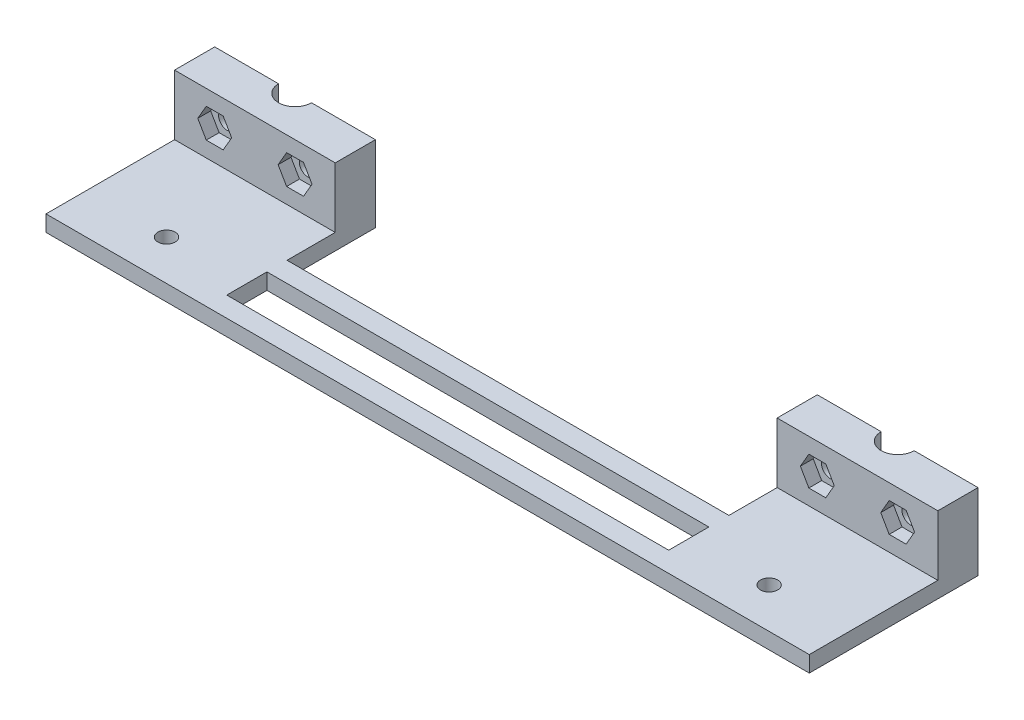
SolidWorks part; units mm, degrees
material "ABS"
ref_plane "Ebene vorne" through (0, 0, 0) normal (0, 0, 1) x (1, 0, 0)
ref_plane "Ebene oben" through (0, 0, 0) normal (0, 1, 0) x (1, 0, 0)
ref_plane "Ebene rechts" through (0, 0, 0) normal (1, 0, 0) x (0, 0, -1)
sketch "Skizze1" plane through (0, 0, 0) normal (0, 1, 0) x (1, 0, 0)
  line L0 (0, 0) -> (75, 0)
  line L1 (0, 0) -> (-75, 0)
  line L2 (55, -10) -> (55, -5)
  line L3 (55, 10) -> (55, 5)
  line L4 (55, -5) -> (55, 5)
  line L5 (-95, 32) -> (-75, 32)
  line L6 (-75, 32) -> (-75, 0)
  line L7 (-75, 32) -> (-55, 32)
  line L8 (-55, 5) -> (-55, 10)
  line L9 (-55, -10) -> (-95, -10)
  line L10 (75, 0) -> (75, 32)
  line L11 (75, 32) -> (55, 32)
  line L12 (-95, -10) -> (-95, 32)
  line L13 (-95, 32) -> (-94.8334, 32.0924)
  line L14 (-55, 32) -> (-55, 10)
  line L15 (95, 32) -> (75, 32)
  line L16 (0, 0) -> (0, 5)
  line L17 (0, 5) -> (-55, 5)
  line L18 (0, 0) -> (0, -5)
  line L19 (0, -5) -> (55, -5)
  line L20 (0, -5) -> (-55, -5)
  line L21 (0, 5) -> (55, 5)
  line L22 (0, 5) -> (0, 10)
  line L23 (0, 10) -> (-55, 10)
  line L24 (0, 10) -> (55, 10)
  line L25 (0, -5) -> (0, -10)
  line L26 (0, -10) -> (55, -10)
  line L27 (0, -10) -> (-55, -10)
  line L28 (-55, 5) -> (-55, -5)
  line L29 (-55, -10) -> (-55, -5)
  line L30 (55, 32) -> (55, 10)
  line L31 (-75, 32) -> (-75, 27.9)
  line L32 (55, -10) -> (95, -10)
  line L33 (95, -10) -> (95, 32)
  line L34 (55, -5) -> (55, 5)
  circle A0 centre (-75, 0) radius 2.15
  circle A1 centre (75, 0) radius 2.15
  arc A2 (-70.9, 32) -> (-79.1, 32) centre (-75, 32) cw
  arc A3 (79.1, 32) -> (70.9, 32) centre (75, 32) cw
  dimension "D5" = 4.3
  dimension "D10" = 4.3
  dimension "D2" = 32
  dimension "D3" = 32
  dimension "D7" = 20
  dimension "D8" = 20
  dimension "D9" = 20
  dimension "D11" = 75
  dimension "D12" = 75
  dimension "D13" = 20
extrude "Aufsatz-Linear austragen1" add sketch "Skizze1" along normal blind 4 contours L6 A2 L5 L12 L9 L29 L28 L1 A0 | L7 A2 L6 A0 L1 L28 L8 L14 | L22 L23 L8 L17 | L24 L22 L21 L3 | L10 A3 L11 L30 L3 L4 L0 A1 | L15 A3 L10 A1 L0 L4 L2 L32 L33 | L25 L26 L2 L19 | L29 L27 L25 L20
sketch "Skizze2" plane through (0, 4, 0) normal (0, 1, 0) x (1, 0, 0)
  line L0 (-95, 32) -> (-95, 22)
  line L1 (-95, -10) -> (-95, 32) construction
  line L2 (-95, 22) -> (-55, 22)
  line L3 (-55, 32) -> (-55, 10) construction
  line L4 (-55, 22) -> (-55, 32)
  line L5 (-55, 32) -> (-70.9, 32)
  line L6 (-79.1, 32) -> (-95, 32)
  line L7 (55, 32) -> (55, 22)
  line L8 (55, 32) -> (55, 10) construction
  line L9 (55, 22) -> (95, 22)
  line L10 (95, -10) -> (95, 32) construction
  line L11 (95, 22) -> (95, 32)
  line L12 (95, 32) -> (79.1, 32)
  line L13 (55, 32) -> (70.9, 32)
  arc A0 (-70.9, 32) -> (-79.1, 32) centre (-75, 32) cw
  arc A1 (70.9, 32) -> (79.1, 32) centre (75, 32) ccw
extrude "Aufsatz-Linear austragen2" add sketch "Skizze2" along normal blind 15
sketch "Skizze3" plane through (0, 0, -22) normal (0, 0, 1) x (1, 0, 0)
  line L0 (-95, 11.5) -> (-55, 11.5)
  line L1 (-95, 19) -> (-95, 4) construction
  line L2 (-55, 19) -> (-55, 4) construction
  line L3 (-75, 11.5) -> (-75, 19)
  line L4 (-95, 19) -> (-55, 19) construction
  line L5 (-75, 11.5) -> (-85, 11.5)
  line L6 (-75, 11.5) -> (-65, 11.5)
  line L7 (95, 11.5) -> (55, 11.5)
  line L8 (-80.7853, 11.5) -> (-82.8927, 15.15)
  line L9 (-82.8927, 15.15) -> (-87.1073, 15.15)
  line L10 (-87.1073, 15.15) -> (-89.2147, 11.5)
  line L11 (-89.2147, 11.5) -> (-87.1073, 7.85)
  line L12 (-87.1073, 7.85) -> (-82.8927, 7.85)
  line L13 (-82.8927, 7.85) -> (-80.7853, 11.5)
  line L14 (-69.2147, 11.5) -> (-67.1073, 7.85)
  line L15 (-67.1073, 7.85) -> (-62.8927, 7.85)
  line L16 (-62.8927, 7.85) -> (-60.7853, 11.5)
  line L17 (-60.7853, 11.5) -> (-62.8927, 15.15)
  line L18 (-62.8927, 15.15) -> (-67.1073, 15.15)
  line L19 (-67.1073, 15.15) -> (-69.2147, 11.5)
  line L20 (95, 19) -> (95, 4) construction
  line L21 (55, 19) -> (55, 4) construction
  line L22 (75, 11.5) -> (75, 19)
  line L23 (55, 19) -> (95, 19) construction
  line L24 (75, 11.5) -> (85, 11.5)
  line L25 (75, 11.5) -> (65, 11.5)
  line L27 (69.2147, 11.5) -> (67.1073, 15.15)
  line L28 (67.1073, 15.15) -> (62.8927, 15.15)
  line L29 (62.8927, 15.15) -> (60.7853, 11.5)
  line L30 (60.7853, 11.5) -> (62.8927, 7.85)
  line L31 (62.8927, 7.85) -> (67.1073, 7.85)
  line L32 (67.1073, 7.85) -> (69.2147, 11.5)
  line L33 (80.7853, 11.5) -> (82.8927, 7.85)
  line L34 (82.8927, 7.85) -> (87.1073, 7.85)
  line L35 (87.1073, 7.85) -> (89.2147, 11.5)
  line L36 (89.2147, 11.5) -> (87.1073, 15.15)
  line L37 (87.1073, 15.15) -> (82.8927, 15.15)
  line L38 (82.8927, 15.15) -> (80.7853, 11.5)
  circle A0 centre (-85, 11.5) radius 3.65 construction
  circle A1 centre (-65, 11.5) radius 3.65 construction
  circle A2 centre (65, 11.5) radius 3.65 construction
  circle A3 centre (85, 11.5) radius 3.65 construction
extrude "Schnitt-Linear austragen1" cut sketch "Skizze3" against normal blind 3.2 contours L9 L10 L0 L8 | L12 L13 L0 L11 | L18 L19 L6 L0 L17 | L15 L16 L0 L6 L14 | L37 L38 L7 L36 | L34 L35 L7 L33 | L28 L29 L7 L25 L27 | L31 L32 L25 L7 L30
sketch "Skizze4" plane through (0, 0, -22) normal (0, 0, 1) x (1, 0, 0)
  line L0 (95, 11.5) -> (55, 11.5)
  line L1 (95, 19) -> (95, 4) construction
  line L2 (55, 19) -> (55, 4) construction
  line L3 (75, 11.5) -> (65, 11.5)
  line L4 (75, 11.5) -> (85, 11.5)
  line L5 (-55, 11.5) -> (-95, 11.5)
  line L6 (-55, 19) -> (-55, 4) construction
  line L7 (-95, 19) -> (-95, 4) construction
  line L8 (-75, 11.5) -> (-85.0818, 11.5)
  line L9 (-75, 11.5) -> (-65, 11.5)
  circle A0 centre (65, 11.5) radius 2.15
  circle A1 centre (85, 11.5) radius 2.15
  circle A2 centre (-65, 11.5) radius 2.15
  circle A3 centre (-85.0818, 11.5) radius 2.15
  dimension "D1" = 4.3
  dimension "D2" = 4.3
  dimension "D3" = 4.3
  dimension "D4" = 4.3
extrude "Schnitt-Linear austragen2" cut sketch "Skizze4" against normal blind 15 contours L8 A3 L5 | L5 A3 L8 | L5 A2 | L5 A2 | L3 A0 L0 | L0 A0 L3 | L0 A1 | L0 A1
equation "\"M4_mutter\"= 7.4mm"
equation "\"M4_loch\"= 4.3mm"
equation "\"M8_loch\"= 8.4mm"
